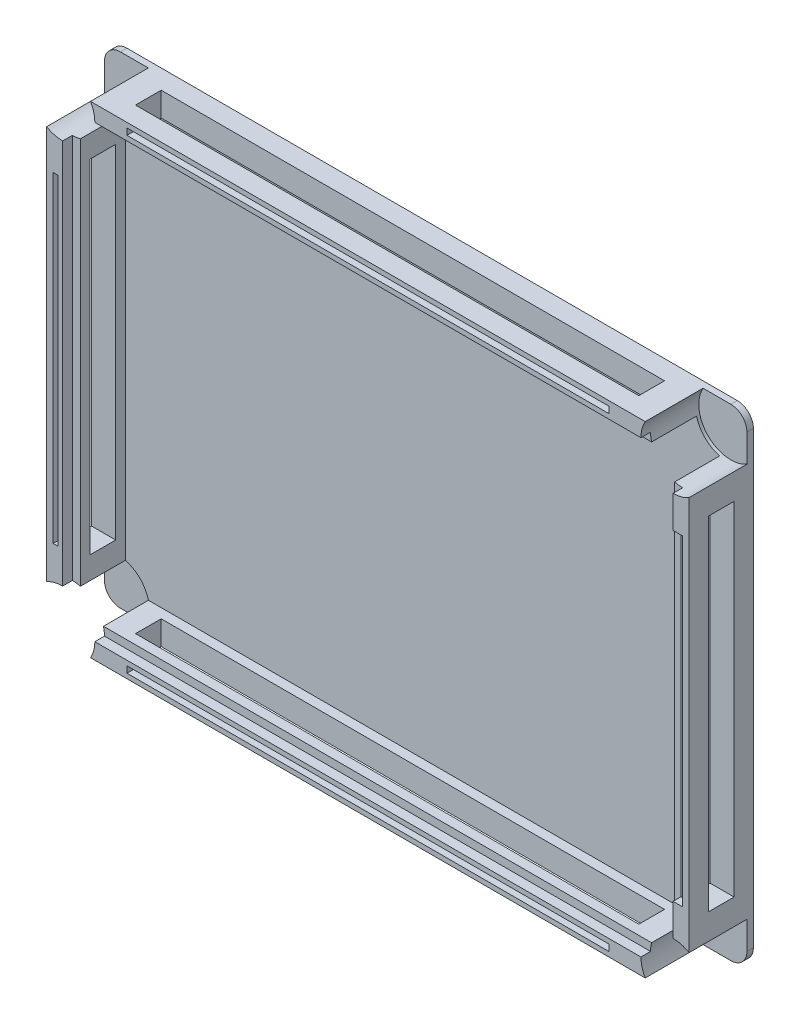
SolidWorks part; units mm, degrees
ref_plane "Plano frontal" through (0, 0, 0) normal (0, 0, 1) x (1, 0, 0)
ref_plane "Plano superior" through (0, 0, 0) normal (0, 1, 0) x (1, 0, 0)
ref_plane "Plano direito" through (0, 0, 0) normal (1, 0, 0) x (0, 0, -1)
sketch "Esboço1" plane through (0, 0, 0) normal (0, 0, 1) x (1, 0, 0)
  line L1 (-100, 75) -> (100, 75)
  line L2 (-100, 75) -> (-100, -75)
  line L3 (-100, -75) -> (100, -75)
  line L4 (100, 75) -> (100, -75)
  line L5 (-100, 75) -> (100, -75) construction
  line L6 (-100, -75) -> (100, 75) construction
  point P0 (0, 0)
  dimension "D1" = 150
  dimension "D2" = 200
extrude "Ressalto-extrusão1" add sketch "Esboço1" along normal blind 20
sketch "Esboço3" plane through (0, 0, 20) normal (0, 0, 1) x (1, 0, 0)
  line L1 (-95, 70) -> (95, 70)
  line L2 (-95, 70) -> (-95, -70)
  line L3 (-95, -70) -> (95, -70)
  line L4 (95, 70) -> (95, -70)
  line L5 (-95, 70) -> (95, -70) construction
  line L6 (-95, -70) -> (95, 70) construction
  point P0 (0, 0)
  dimension "D1" = 190
  dimension "D2" = 140
sketch "Esboço4" plane through (0, 0, 20) normal (0, 0, 1) x (1, 0, 0)
  line L1 (-92.5, 67.5) -> (92.5, 67.5)
  line L2 (-92.5, 67.5) -> (-92.5, -67.5)
  line L3 (-92.5, -67.5) -> (92.5, -67.5)
  line L4 (92.5, 67.5) -> (92.5, -67.5)
  line L5 (-92.5, 67.5) -> (92.5, -67.5) construction
  line L6 (-92.5, -67.5) -> (92.5, 67.5) construction
  point P0 (0, 0)
  dimension "D1" = 185
  dimension "D2" = 135
extrude "Corte-extrusão2" cut sketch "Esboço4" against normal blind 17
extrude "Corte-extrusão3" cut sketch "Esboço3" against normal blind 3
sketch "Esboço6" plane through (0, 0, 20) normal (0, 0, 1) x (1, 0, 0)
  circle A0 centre (-95, 70) radius 10
  circle A1 centre (95, 70) radius 10
  circle A2 centre (-95, -70) radius 10
  circle A3 centre (95, -70) radius 10
extrude "Corte-extrusão4" cut sketch "Esboço6" against normal blind 18
fillet "Filete4" radius 5 1 edges at (-100, 75, 1)
fillet "Filete5" radius 5 1 edges at (100, 75, 1)
fillet "Filete6" radius 5 1 edges at (100, -75, 1)
fillet "Filete7" radius 5 1 edges at (-100, -75, 1)
sketch "Esboço7" plane through (0, -75, 0) normal (0, -1, 0) x (1, 0, 0)
  line L0 (-86.3397, 20) -> (86.3397, 20) construction
  line L1 (-78.3397, 14) -> (78.3397, 14)
  line L2 (-78.3397, 14) -> (-78.3397, 6)
  line L3 (-78.3397, 6) -> (78.3397, 6)
  line L4 (78.3397, 14) -> (78.3397, 6)
  line L5 (-95, 0) -> (95, 0) construction
  line L6 (-86.3397, 20) -> (-86.3397, 2) construction
  line L7 (86.3397, 2) -> (86.3397, 20) construction
  dimension "D1" = 6
  dimension "D2" = 6
  dimension "D3" = 8
  dimension "D4" = 8
extrude "Corte-extrusão5" cut sketch "Esboço7" against normal blind 300
sketch "Esboço8" plane through (-100, 0, 0) normal (-1, 0, 0) x (0, 0, 1)
  line L0 (0, 70) -> (0, -70) construction
  line L1 (6, 53.3397) -> (14, 53.3397)
  line L2 (6, 53.3397) -> (6, -53.3397)
  line L3 (6, -53.3397) -> (14, -53.3397)
  line L4 (14, 53.3397) -> (14, -53.3397)
  line L5 (20, 61.3397) -> (20, -61.3397) construction
  line L6 (20, 61.3397) -> (2, 61.3397) construction
  line L7 (2, -61.3397) -> (20, -61.3397) construction
  dimension "D1" = 6
  dimension "D2" = 6
  dimension "D3" = 8
  dimension "D4" = 8
extrude "Corte-extrusão6" cut sketch "Esboço8" against normal blind 300
sketch "Esboço9" plane through (0, 0, 3) normal (0, 0, 1) x (1, 0, 0)
  line L0 (-85, 70) -> (85, 70)
  line L1 (95, 60) -> (95, -60)
  line L2 (85, -70) -> (-85, -70)
  line L3 (-95, -60) -> (-95, 60)
  arc A0 (-95, 60) -> (-85, 70) centre (-95, 70) ccw
  arc A1 (85, 70) -> (95, 60) centre (95, 70) ccw
  arc A2 (95, -60) -> (85, -70) centre (95, -70) ccw
  arc A3 (-85, -70) -> (-95, -60) centre (-95, -70) ccw
  point P17 (0, 0)
sketch "Esboço13" plane through (0, 0, 2) normal (0, 0, 1) x (1, 0, 0)
  line L0 (-100, -61.3397) -> (-100, -70)
  line L1 (-86.3397, -75) -> (-95, -75)
  arc A0 (-95, -75) -> (-100, -70) centre (-95, -70) cw
  arc A1 (-100, -61.3397) -> (-86.3397, -75) centre (-95, -70) cw
sketch "Esboço15" plane through (0, 0, 20) normal (0, 0, 1) x (1, 0, 0)
  line L0 (-98, -50) -> (-98, 50)
  line L1 (-75, 73.5) -> (75, 73.5)
  line L2 (-75, 73.5) -> (-75, 71.5)
  line L3 (-75, 71.5) -> (75, 71.5)
  line L4 (75, 73.5) -> (75, 71.5)
  line L5 (-98, -50) -> (-96.5, -50)
  line L6 (86.3397, 75) -> (-86.3397, 75) construction
  line L7 (-96.5, -50) -> (-96.5, 50)
  line L8 (-75, -71.5) -> (75, -71.5)
  line L9 (-75, -71.5) -> (-75, -73.5)
  line L10 (-75, -73.5) -> (75, -73.5)
  line L11 (75, -71.5) -> (75, -73.5)
  line L12 (-85, -70) -> (85, -70) construction
  line L13 (-98, 50) -> (-96.5, 50)
  line L14 (100, -61.3397) -> (100, 61.3397) construction
  line L15 (94.5, -50) -> (94.5, 50)
  line L16 (94.5, -50) -> (98, -50)
  line L17 (98, -50) -> (98, 50)
  line L18 (94.5, 50) -> (98, 50)
  line L19 (92.5, -60.3175) -> (92.5, 60.3175) construction
  line L20 (-100, 61.3397) -> (-100, -61.3397) construction
  line L21 (-95, -60) -> (-95, 60) construction
  arc A0 (-85, 70) -> (-86.3397, 75) centre (-95, 70) ccw construction
  arc A1 (-86.3397, -75) -> (-85, -70) centre (-95, -70) ccw construction
  arc A2 (85, -70) -> (86.3397, -75) centre (95, -70) ccw construction
  arc A3 (-86.3397, -75) -> (-100, -61.3397) centre (-95, -70) ccw construction
  arc A4 (86.3397, 75) -> (100, 61.3397) centre (95, 70) ccw construction
  arc A5 (-100, 61.3397) -> (-95, 60) centre (-95, 70) ccw construction
  arc A6 (100, -61.3397) -> (95, -60) centre (95, -70) ccw construction
  dimension "D1" = 2
  dimension "D2" = 1.5
  dimension "D3" = 150
  dimension "D4" = 20
  dimension "D5" = 1.5
  dimension "D6" = 20
  dimension "D7" = 20
  dimension "D8" = 100
  dimension "D9" = 20
  dimension "D10" = 20
  dimension "D11" = 20
  dimension "D12" = 20
  dimension "D13" = 2
  dimension "D14" = 2
  dimension "D15" = 2
  dimension "D16" = 1.5
  dimension "D18" = 3.5
extrude "Corte-extrusão7" cut sketch "Esboço15" against normal blind 2.5
